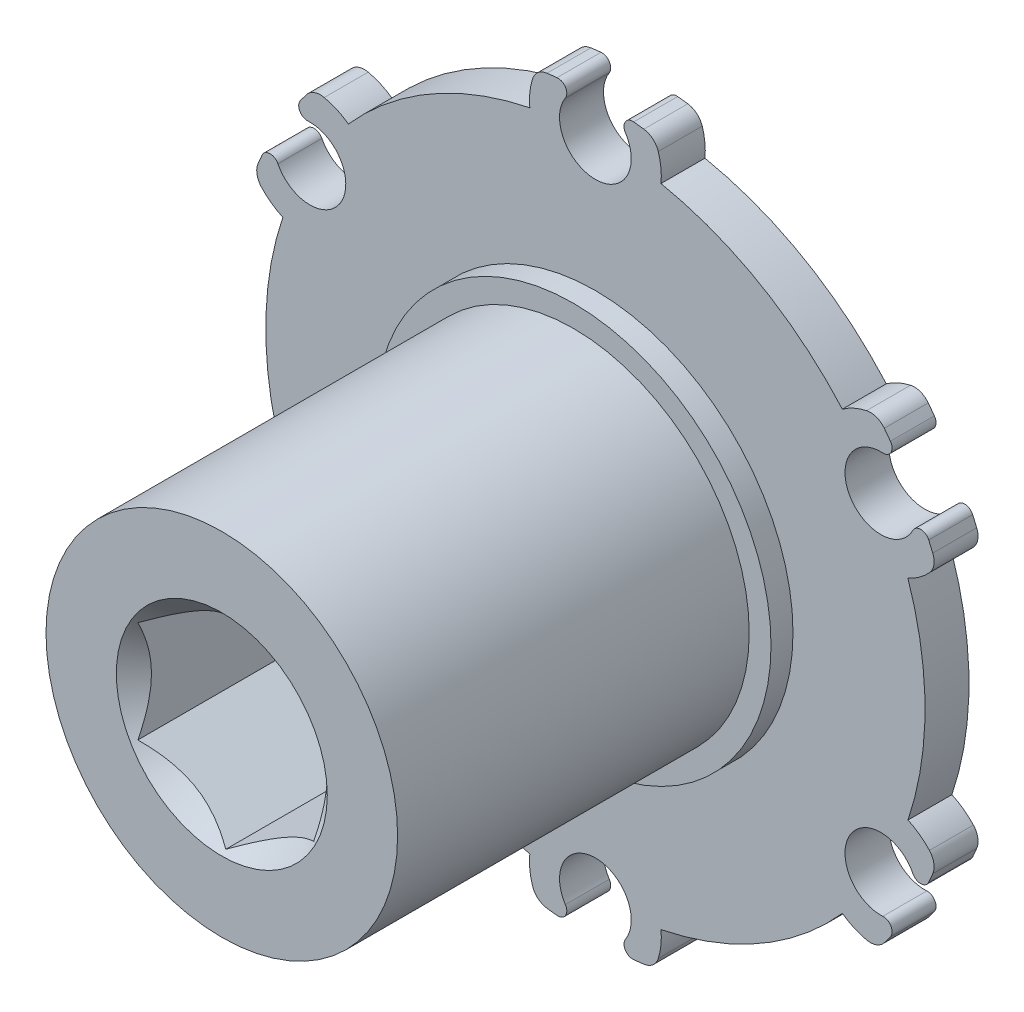
SolidWorks part; units mm, degrees
material "AISI 316 Annealed Stainless Steel Bar (SS)"
ref_plane "Front Plane" through (0, 0, 0) normal (0, 0, 1) x (1, 0, 0)
ref_plane "Top Plane" through (0, 0, 0) normal (0, 1, 0) x (1, 0, 0)
ref_plane "Right Plane" through (0, 0, 0) normal (1, 0, 0) x (0, 0, -1)
sketch "Sketch1" plane through (0, 0, 0) normal (0, 0, 1) x (1, 0, 0)
  circle A0 centre (0, 0) radius 23.8125 construction
  circle A1 centre (0, 23.8125) radius 2.5908
  circle A2 centre (20.6222, 11.9063) radius 2.5908
  circle A3 centre (20.6222, -11.9062) radius 2.5908
  circle A4 centre (0, -23.8125) radius 2.5908
  circle A5 centre (-20.6222, -11.9063) radius 2.5908
  circle A6 centre (-20.6222, 11.9062) radius 2.5908
  circle A7 centre (0, 0) radius 6.35
  circle A11 centre (0, 0) radius 26.3525
  circle A12 centre (0, 23.8125) radius 2.54 construction
  point P17 (0, 0)
  dimension "D1" = 47.625
  dimension "D2" = 5.1816
  dimension "D4" = 12.7
  dimension "D5" = 5.08
  dimension "D3" = 6
extrude "Boss-Extrude2" add sketch "Sketch1" along normal blind 3.175 contours A2 A11 A1 A6 A5 A4 A3 A7
fillet "Fillet1" radius 0.635 12 edges at (-23.0857, 12.7084, 1.5875) (-22.5487, 13.6386, 1.5875) (-22.5487, -13.6386, 1.5875) (-23.0857, -12.7084, 1.5875) (0.537, -26.347, 1.5875) (-0.537, -26.347, 1.5875) (23.0857, -12.7084, 1.5875) (22.5487, -13.6386, 1.5875) (22.5487, 13.6386, 1.5875) (23.0857, 12.7084, 1.5875) (-0.537, 26.347, 1.5875) (0.537, 26.347, 1.5875)
sketch "Sketch2" plane through (0, 0, 3.175) normal (0, 0, 1) x (1, 0, 0)
  circle A0 centre (0, 23.8125) radius 4.7625
  circle A1 centre (-20.6222, 11.9062) radius 4.7625
  circle A2 centre (-20.6222, -11.9063) radius 4.7625
  circle A3 centre (0, -23.8125) radius 4.7625
  circle A4 centre (20.6222, -11.9062) radius 4.7625
  circle A5 centre (20.6222, 11.9063) radius 4.7625
  circle A6 centre (0, 0) radius 23.8125
  circle A7 centre (0, 0) radius 26.3525
  arc M3 (-2.7683, 26.2067) -> (-21.3115, 15.5008) centre (0, 0) ccw
  arc M7 (-24.0798, 10.7059) -> (-24.0798, -10.7059) centre (0, 0) ccw
  arc M11 (-21.3115, -15.5008) -> (-2.7683, -26.2067) centre (0, 0) ccw
  arc M15 (2.7683, -26.2067) -> (21.3115, -15.5008) centre (0, 0) ccw
  arc M19 (24.0798, -10.7059) -> (24.0798, 10.7059) centre (0, 0) ccw
  arc M23 (21.3115, 15.5008) -> (2.7683, 26.2067) centre (0, 0) ccw
  dimension "D1" = 9.525
extrude "Cut-Extrude2" cut sketch "Sketch2" against normal blind 3.175 contours A6 A0 A1 M3 | A6 A5 A0 M23 | A6 A4 A5 M19 | A6 A3 A4 M15 | A6 A2 A3 M11 | A6 A1 A2 M7
fillet "Fillet2" radius 1.27 12 edges at (-24.639, 9.3475, 1.5875) (-20.4146, 16.6642, 1.5875) (-24.639, -9.3475, 1.5875) (-20.4146, -16.6642, 1.5875) (-4.2243, -26.0117, 1.5875) (4.2243, -26.0117, 1.5875) (20.4146, -16.6642, 1.5875) (24.639, -9.3475, 1.5875) (24.639, 9.3475, 1.5875) (20.4146, 16.6642, 1.5875) (4.2243, 26.0117, 1.5875) (-4.2243, 26.0117, 1.5875)
sketch "Sketch3" plane through (0, 0, 3.175) normal (0, 0, 1) x (1, 0, 0)
  circle A0 centre (0, 0) radius 14.2748
  circle A1 centre (0, 0) radius 6.35
  dimension "D1" = 12.7
  dimension "D2" = 28.5496
extrude "Boss-Extrude3" add sketch "Sketch3" along normal blind 1.5875
ref_plane "Plane1" through (0, 0, 1.5875) normal (0, 0, 1) x (1, 0, 0)
mirror "Mirror1" about plane through (0, 0, 1.5875) normal (0, 0, 1) of "Boss-Extrude3"
sketch "Sketch4" plane through (0, 0, 4.7625) normal (0, 0, 1) x (1, 0, 0)
  circle A0 centre (0, 0) radius 12.7
  circle A1 centre (0, 0) radius 6.35
  dimension "D1" = 25.4
  dimension "D2" = 12.7
extrude "Boss-Extrude4" add sketch "Sketch4" along normal blind 25.4
chamfer "Chamfer1" distance 1.27 angle 45 2 edges at (6.35, 0, -1.5875) (6.35, 0, 30.1625)
sketch "Sketch5" plane through (0, 0, 30.1625) normal (0, 0, 1) x (1, 0, 0)
  line L1 (0, 7.3323) -> (-6.35, 3.6662)
  line L2 (-6.35, 3.6662) -> (-6.35, -3.6662)
  line L3 (-6.35, -3.6662) -> (0, -7.3323)
  line L4 (0, -7.3323) -> (6.35, -3.6662)
  line L5 (6.35, -3.6662) -> (6.35, 3.6662)
  line L6 (6.35, 3.6662) -> (0, 7.3323)
  circle A0 centre (0, 0) radius 6.35 construction
  circle A1 centre (0, 0) radius 6.35 construction
extrude "Cut-Extrude3" cut sketch "Sketch5" against normal through all
